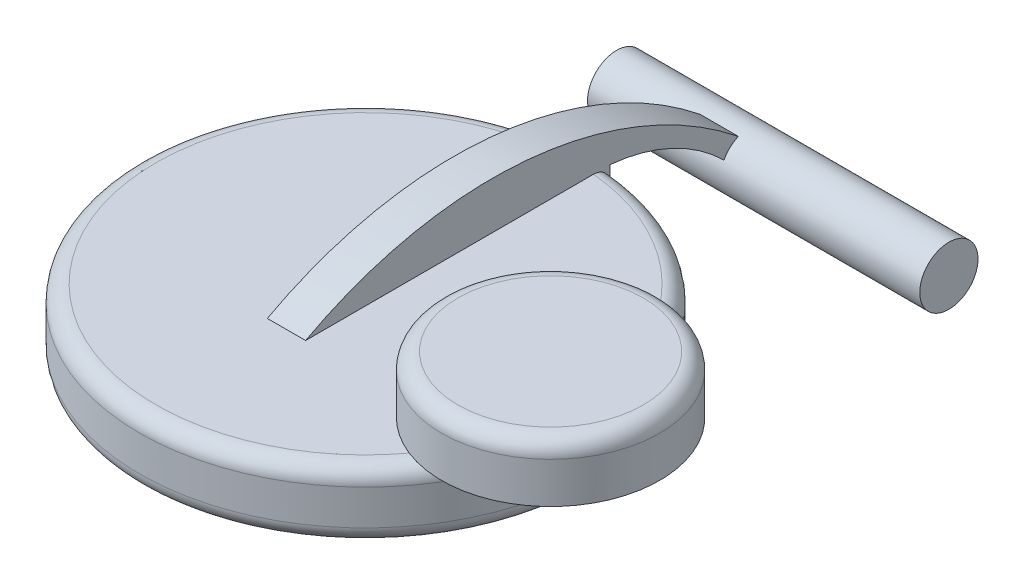
SolidWorks part; units mm, degrees
material "6061 Alloy"
ref_plane "Front Plane" through (0, 0, 0) normal (0, 0, 1) x (1, 0, 0)
ref_plane "Top Plane" through (0, 0, 0) normal (0, 1, 0) x (1, 0, 0)
ref_plane "Right Plane" through (0, 0, 0) normal (1, 0, 0) x (0, 0, -1)
sketch "Sketch1" plane through (0, 0, 0) normal (1, 0, 0) x (0, 0, -1)
  circle A0 centre (0, 0) radius 2.2606
  dimension "D1" = 4.5212
extrude "Boss-Extrude1" add sketch "Sketch1" along normal blind 25.8064
ref_plane "Plane1" through (7.366, 0, 0) normal (1, 0, 0) x (0, 0, -1)
sketch "Sketch2" plane through (7.366, 0, 0) normal (1, 0, 0) x (0, 0, -1)
  line L0 (-34.4932, 5.1562) -> (-10.795, 5.1562)
  line L1 (2.4867, 0) -> (-2.4867, 0) construction
  line L2 (0, 2.4867) -> (0, -2.4867) construction
  line L3 (0, 1.3415) -> (0, -1.4266)
  arc A0 (-10.795, 5.1562) -> (0, -1.4266) centre (-12.1711, -9.243) cw
  arc A1 (-34.4932, 5.1562) -> (0, 1.3415) centre (-20.0046, -21.6892) cw
  point P10 (0, 0)
  point P11 (0, 0)
  dimension "D4" = 30.5057
  dimension "D5" = 14.4648
  dimension "D1" = 23.6982
  dimension "D2" = 5.1562
  dimension "D3" = 10.795
extrude "Boss-Extrude2" add sketch "Sketch2" along normal blind 2.9718
sketch "Sketch3" plane through (0, 5.1562, 0) normal (0, -1, 0) x (1, 0, 0)
  line L0 (8.8519, 34.4932) -> (8.8519, 10.795) construction
  line L1 (10.3378, 34.4932) -> (7.366, 34.4932) construction
  line L2 (10.3378, 10.795) -> (7.366, 10.795) construction
  circle A0 centre (8.8519, 28.3464) radius 17.5514
  point P8 (0, 0)
  point P9 (0, 0)
  dimension "D1" = 35.1028
extrude "Boss-Extrude3" add sketch "Sketch3" along normal blind 5.2832
fillet "Fillet1" radius 1.27 2 edges at (8.8519, 5.1562, 45.8978) (8.8519, -0.127, 10.795)
sketch "Sketch4" plane through (0, 5.1562, 0) normal (0, 1, 0) x (1, 0, 0)
  line L0 (8.8519, -34.4932) -> (25.0322, -30.1577) construction
  line L1 (10.3378, -34.4932) -> (7.366, -34.4932) construction
  arc A0 (7.366, -12.1329) -> (10.3378, -12.1329) centre (8.8519, -28.3464) ccw construction
  circle A1 centre (25.0322, -30.1577) radius 8.4709
  dimension "D2" = 16.9418
  dimension "D1" = 15
extrude "Boss-Extrude4" add sketch "Sketch4" along normal blind 4.445
fillet "Fillet2" radius 1.27 1 edges at (25.0322, 9.6012, 38.6286)
